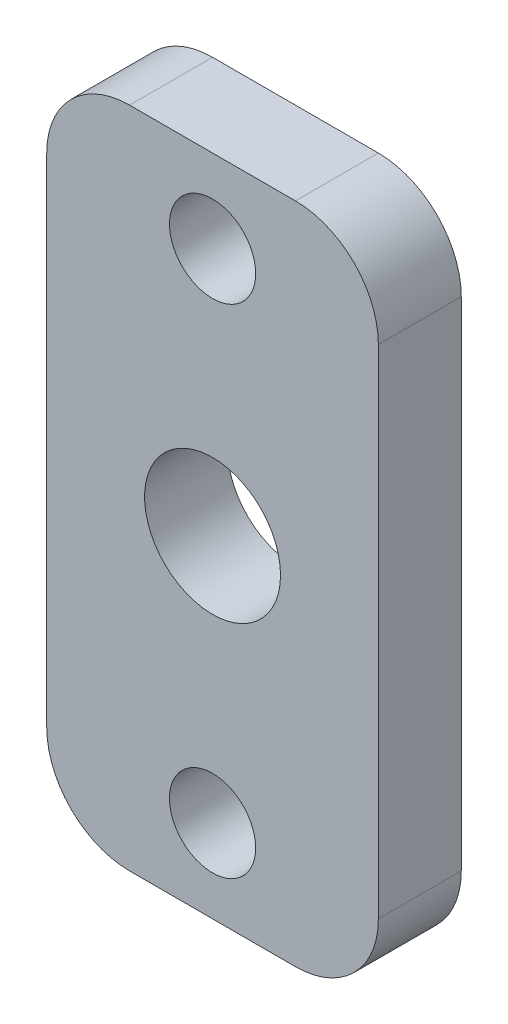
SolidWorks part; units mm, degrees
material "Acrílico (médio-alto impacto)"
ref_plane "Plano frontal" through (0, 0, 0) normal (0, 0, 1) x (1, 0, 0)
ref_plane "Plano superior" through (0, 0, 0) normal (0, 1, 0) x (1, 0, 0)
ref_plane "Plano direito" through (0, 0, 0) normal (1, 0, 0) x (0, 0, -1)
sketch "Esboço1" plane through (0, 0, 0) normal (0, 0, 1) x (1, 0, 0)
  line L1 (-10, 20) -> (10, 20)
  line L2 (-10, 20) -> (-10, -20)
  line L3 (-10, -20) -> (10, -20)
  line L4 (10, 20) -> (10, -20)
  line L5 (-10, 20) -> (10, -20) construction
  line L6 (-10, -20) -> (10, 20) construction
  point P0 (0, 0)
  dimension "D1" = 20
  dimension "D2" = 40
extrude "Ressalto-extrusão1" add sketch "Esboço1" along normal mid plane 5
sketch "Esboço2" plane through (0, 0, 2.5) normal (0, 0, 1) x (1, 0, 0)
  circle A0 centre (0, 0) radius 4.1
  dimension "D1" = 8.2
extrude "Corte-extrusão1" cut sketch "Esboço2" against normal through all
sketch "Esboço3" plane through (0, 0, 2.5) normal (0, 0, 1) x (1, 0, 0)
  line L0 (0, 20) -> (0, -20) construction
  line L1 (10, 20) -> (-10, 20) construction
  line L2 (-10, -20) -> (10, -20) construction
  circle A0 centre (0, 15) radius 2.6
  point P8 (0, 0)
  dimension "D1" = 5.2
  dimension "D2" = 15
extrude "Corte-extrusão2" cut sketch "Esboço3" against normal through all
mirror "Espelhar1" about plane through (0, 0, 0) normal (0, 1, 0) of "Corte-extrusão2"
fillet "Filete1" radius 5 4 edges at (10, -20, 0) (-10, -20, 0) (10, 20, 0) (-10, 20, 0)
